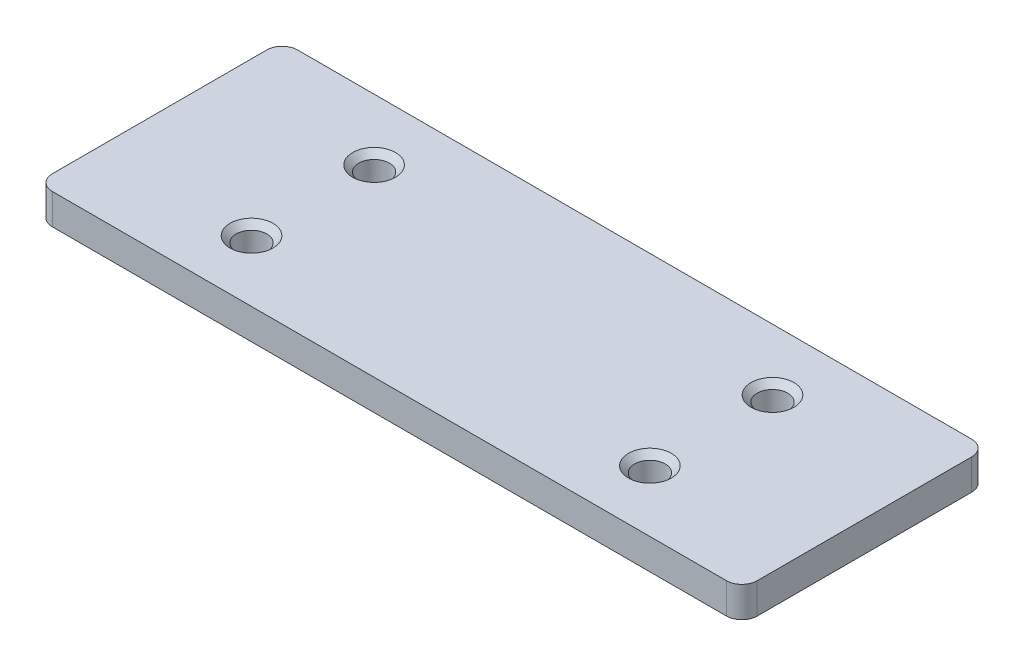
SolidWorks part; units mm, degrees
ref_plane "Front Plane" through (0, 0, 0) normal (0, 0, 1) x (1, 0, 0)
ref_plane "Top Plane" through (0, 0, 0) normal (0, 1, 0) x (1, 0, 0)
ref_plane "Right Plane" through (0, 0, 0) normal (1, 0, 0) x (0, 0, -1)
sketch "Sketch1" plane through (0, 0, 0) normal (0, 1, 0) x (1, 0, 0)
  line L0 (0, 10.0802) -> (0, 0) construction
  line L1 (-57.5, -20) -> (57.5, -20)
  line L2 (-57.5, -20) -> (-57.5, 20)
  line L3 (-57.5, 20) -> (57.5, 20)
  line L4 (57.5, -20) -> (57.5, 20)
  line L5 (-57.5, -20) -> (57.5, 20) construction
  line L6 (-57.5, 20) -> (57.5, -20) construction
  line L7 (0, 0) -> (12.3519, 0) construction
  circle A0 centre (-32.5, 10) radius 2.5
  circle A1 centre (-32.5, -10) radius 2.5
  circle A2 centre (32.5, -10) radius 2.5
  circle A3 centre (32.5, 10) radius 2.5
  point P0 (0, 0)
  point P13 (0, 0)
  dimension "D3" = 10
  dimension "D4" = 5
  dimension "D5" = 25
  dimension "D6" = 10
  dimension "D1" = 115
  dimension "D2" = 40
extrude "Boss-Extrude1" add sketch "Sketch1" along normal blind 5
fillet "Fillet1" radius 2.5 4 edges at (57.5, 2.5, 20) (-57.5, 2.5, -20) (57.5, 2.5, -20) (-57.5, 2.5, 20)
chamfer "Chamfer1" distance 1 angle 45 4 edges at (32.5, 5, 7.5) (32.5, 5, -12.5) (-32.5, 5, 12.5) (-32.5, 5, -7.5)
